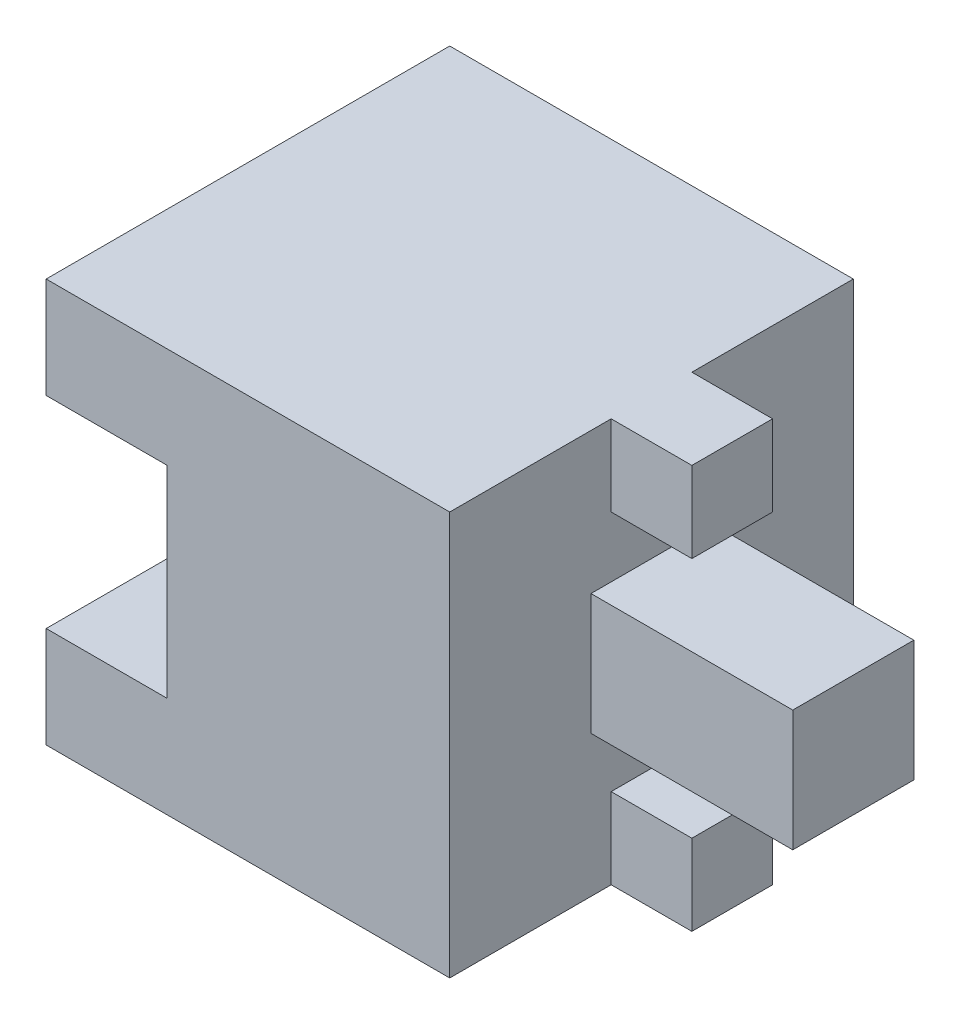
SolidWorks part; units mm, degrees
ref_plane "Front Plane" through (0, 0, 0) normal (0, 0, 1) x (1, 0, 0)
ref_plane "Top Plane" through (0, 0, 0) normal (0, 1, 0) x (1, 0, 0)
ref_plane "Right Plane" through (0, 0, 0) normal (1, 0, 0) x (0, 0, -1)
sketch "Sketch1" plane through (0, 0, 0) normal (0, 1, 0) x (1, 0, 0)
  line L1 (-5, -5) -> (5, -5)
  line L2 (-5, -5) -> (-5, 5)
  line L3 (-5, 5) -> (5, 5)
  line L4 (5, -5) -> (5, 5)
  line L5 (-5, -5) -> (5, 5) construction
  line L6 (-5, 5) -> (5, -5) construction
  point P0 (0, 0)
  dimension "D1" = 10
  dimension "D2" = 10
extrude "Boss-Extrude1" add sketch "Sketch1" along normal mid plane 10
sketch "Sketch2" plane through (0, 0, 5) normal (0, 0, 1) x (1, 0, 0)
  line L0 (-7.1123, 0) -> (7.1123, 0) construction
  line L1 (-5, 5) -> (-5, -5) construction
  line L2 (-2, -2.5) -> (-5, -2.5)
  line L3 (-2, -2.5) -> (-2, 2.5)
  line L4 (-2, 2.5) -> (-5, 2.5)
  line L5 (-5, -2.5) -> (-5, 2.5)
  line L6 (-2, -2.5) -> (-5, 2.5) construction
  line L7 (-2, 2.5) -> (-5, -2.5) construction
  point P0 (-3.5, 0)
  point P4 (0, 0)
  dimension "D1" = 3
  dimension "D2" = 5
extrude "Cut-Extrude1" cut sketch "Sketch2" against normal through all
sketch "Sketch3" plane through (5, 0, 0) normal (1, 0, 0) x (0, 0, -1)
  line L1 (-1.5, -1.5) -> (1.5, -1.5)
  line L2 (-1.5, -1.5) -> (-1.5, 1.5)
  line L3 (-1.5, 1.5) -> (1.5, 1.5)
  line L4 (1.5, -1.5) -> (1.5, 1.5)
  line L5 (-1.5, -1.5) -> (1.5, 1.5) construction
  line L6 (-1.5, 1.5) -> (1.5, -1.5) construction
  point P0 (0, 0)
  dimension "D1" = 3
  dimension "D2" = 3
extrude "Boss-Extrude2" add sketch "Sketch3" along normal blind 5
sketch "Sketch4" plane through (5, 0, 0) normal (1, 0, 0) x (0, 0, -1)
  line L0 (0, 5.6129) -> (0, -5.6129) construction
  line L1 (-6.8847, 0) -> (6.8847, 0) construction
  line L2 (-5, 5) -> (5, 5) construction
  line L3 (-1, 3) -> (1, 3)
  line L4 (-1, 3) -> (-1, 5)
  line L5 (-1, 5) -> (1, 5)
  line L6 (1, 3) -> (1, 5)
  line L7 (-1, 3) -> (1, 5) construction
  line L8 (-1, 5) -> (1, 3) construction
  point P0 (0, 4)
  point P4 (0, 0)
  point P8 (0, 0)
  dimension "D1" = 2
  dimension "D2" = 2
extrude "Boss-Extrude3" add sketch "Sketch4" along normal blind 2
mirror "Mirror1" about plane through (0, 0, 0) normal (0, 1, 0) of "Boss-Extrude3"
